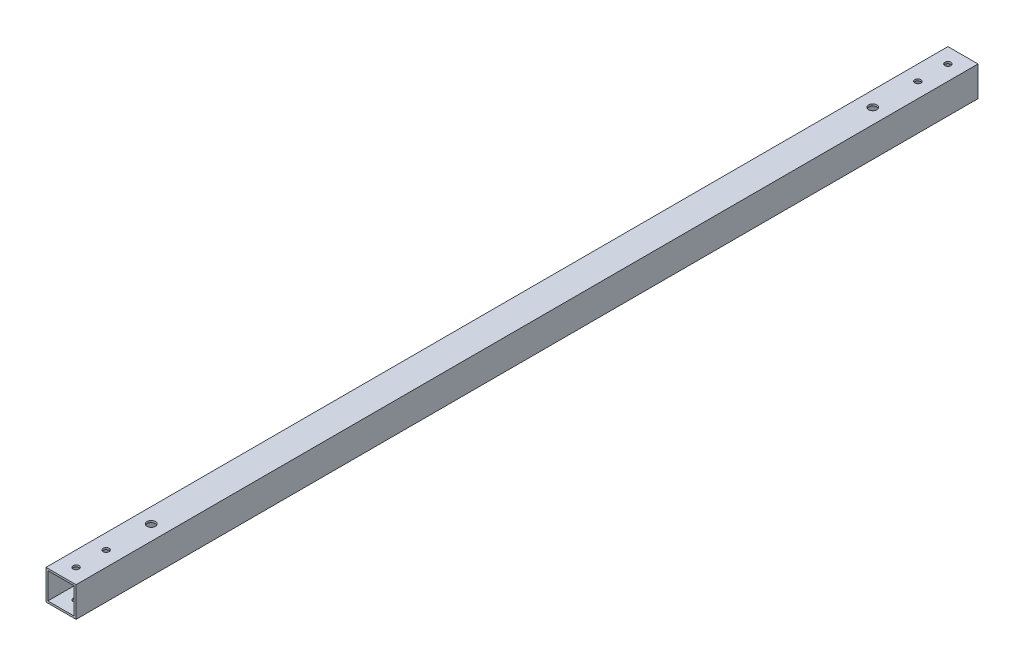
SolidWorks part; units mm, degrees
ref_plane "Front Plane" through (0, 0, 0) normal (0, 0, 1) x (1, 0, 0)
ref_plane "Top Plane" through (0, 0, 0) normal (0, 1, 0) x (1, 0, 0)
ref_plane "Right Plane" through (0, 0, 0) normal (1, 0, 0) x (0, 0, -1)
sketch "Sketch1" plane through (0, 0, 0) normal (0, 0, 1) x (1, 0, 0)
  line L1 (0, 0) -> (25.4, 0)
  line L2 (0, 0) -> (0, 25.4)
  line L3 (0, 25.4) -> (25.4, 25.4)
  line L4 (25.4, 0) -> (25.4, 25.4)
  line L5 (1.5875, 1.5875) -> (23.8125, 1.5875)
  line L6 (1.5875, 1.5875) -> (1.5875, 23.8125)
  line L7 (1.5875, 23.8125) -> (23.8125, 23.8125)
  line L8 (23.8125, 1.5875) -> (23.8125, 23.8125)
  dimension "D1" = 25.4
  dimension "D2" = 1.5875
  dimension "D3" = 1.5875
  dimension "D4" = 1.5875
  dimension "D5" = 1.5875
extrude "Boss-Extrude1" add sketch "Sketch1" along normal blind 762
sketch "Sketch2" plane through (25.4, 0, 0) normal (1, 0, 0) x (0, 0, -1)
  line L0 (-762, 0) -> (-762, 25.4) construction
  line L1 (-762, 25.4) -> (0, 25.4) construction
  circle A0 centre (-749.3, 12.7) radius 6.35
  dimension "D2" = 12.7
  dimension "D1" = 12.7
  dimension "D3" = 12.7
sketch "Sketch3" plane through (0, 25.4, 0) normal (0, 1, 0) x (1, 0, 0)
  line L0 (0, -762) -> (0, 0) construction
  line L2 (25.4, 0) -> (0, 0) construction
  line L3 (0, -381) -> (25.4, -381) construction
  line L4 (25.4, -762) -> (25.4, 0) construction
  circle A1 centre (12.7, -12.7) radius 2.54
  circle A5 centre (12.7, -38.1) radius 2.54
  circle A6 centre (12.7, -76.2) radius 3.556
  circle A7 centre (12.7, -685.8) radius 3.556
  circle A8 centre (12.7, -723.9) radius 2.54
  circle A9 centre (12.7, -749.3) radius 2.54
  dimension "D8" = 7.112
  dimension "D4" = 12.7
  dimension "D6" = 38.1
  dimension "D7" = 25.4
extrude "Cut-Extrude2" cut sketch "Sketch3" against normal through all
